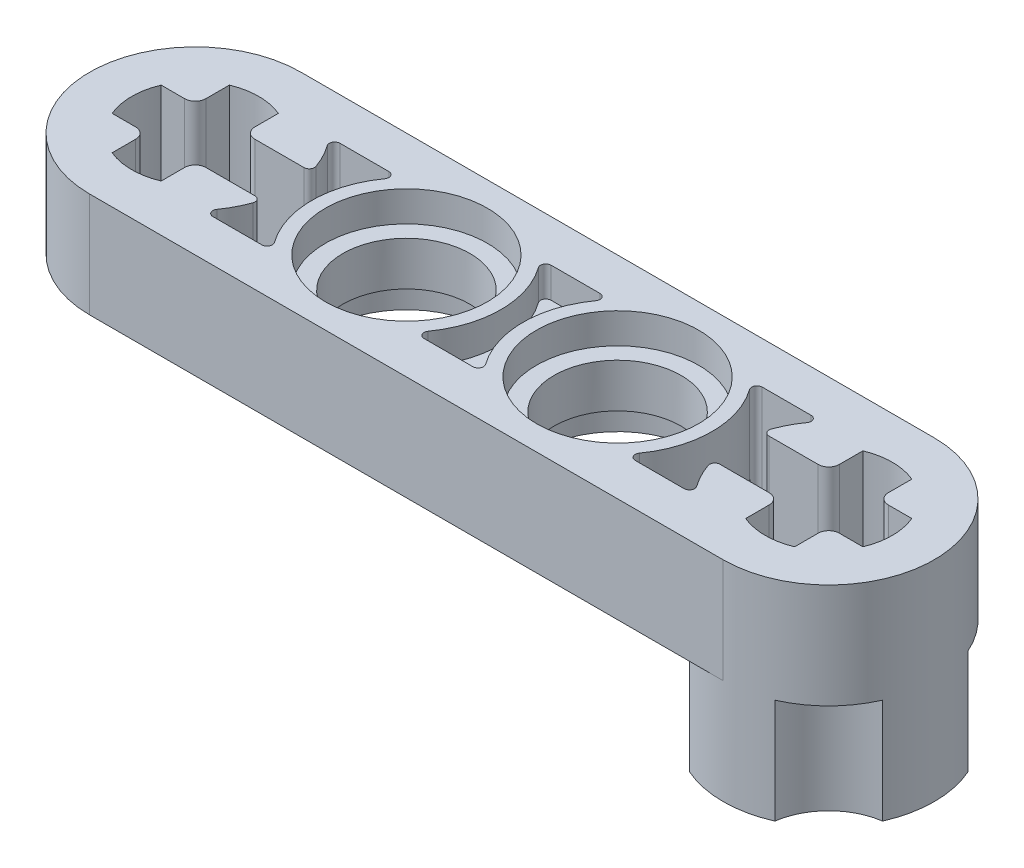
SolidWorks part; units mm, degrees
ref_plane "Front" through (0, 0, 0) normal (0, 0, 1) x (1, 0, 0)
ref_plane "Top" through (0, 0, 0) normal (0, 1, 0) x (1, 0, 0)
ref_plane "Right" through (0, 0, 0) normal (1, 0, 0) x (0, 0, -1)
sketch "Sketch1" plane through (0, 0, 0) normal (0, 1, 0) x (1, 0, 0)
  line L0 (0, 0) -> (0, 8.6394) construction
  line L1 (-11.9063, 3.9687) -> (11.9063, 3.9687)
  line L2 (11.9063, -3.9687) -> (-11.9063, -3.9687)
  line L3 (0, 0) -> (18.7139, 0) construction
  arc A0 (11.9063, 3.9687) -> (11.9063, -3.9687) centre (11.9063, 0) cw
  arc A1 (-11.9063, 3.9687) -> (-11.9063, -3.9687) centre (-11.9063, 0) ccw
  point P6 (0, 3.9687)
  point P11 (0, -3.9688)
  dimension "D1" = 7.9375
  dimension "D2" = 31.75
extrude "Base-Extrude" add sketch "Sketch1" along normal mid plane 3.937
sketch "Sketch2" plane through (0, 1.9685, 0) normal (0, 1, 0) x (-1, 0, 0)
  circle A0 centre (3.9688, 0) radius 2.3876
  dimension "D1" = 4.7752
  dimension "D2" = 3.9688
extrude "Cut-Extrude1" cut sketch "Sketch2" against normal through all
sketch "Sketch3" plane through (0, 1.9685, 0) normal (0, 1, 0) x (-1, 0, 0)
  circle A0 centre (3.9688, 0) radius 3.048
  dimension "D1" = 6.096
extrude "Cut-Extrude2" cut sketch "Sketch3" against normal blind 1.143
sketch "Sketch4" plane through (0, -1.9685, 0) normal (0, -1, 0) x (1, 0, 0)
  circle A0 centre (-3.9688, 0) radius 3.048
  dimension "D1" = 6.096
extrude "Cut-Extrude3" cut sketch "Sketch4" against normal blind 1.143
pattern_linear "LPattern1" count 2 spacing 7.9375 along (1, 0, 0) of "Cut-Extrude3", "Cut-Extrude2", "Cut-Extrude1"
sketch "Sketch5" plane through (0, 1.9685, 0) normal (0, 1, 0) x (-1, 0, 0)
  line L0 (11.9063, 0) -> (11.9063, -5.3472) construction
  line L1 (11.9063, 0) -> (8.2567, 0) construction
  line L2 (10.9855, -2.2029) -> (10.9855, -0.9207)
  line L3 (10.9855, -0.9207) -> (9.7033, -0.9207)
  line L4 (10.9855, 0.9208) -> (9.7033, 0.9208)
  line L5 (10.9855, 2.2029) -> (10.9855, 0.9208)
  line L6 (12.827, 2.2029) -> (12.827, 0.9208)
  line L7 (12.827, 0.9208) -> (14.1092, 0.9208)
  line L8 (12.827, -0.9207) -> (14.1092, -0.9207)
  line L9 (12.827, -2.2029) -> (12.827, -0.9207)
  arc A0 (10.9855, -2.2029) -> (12.827, -2.2029) centre (11.9063, 0) ccw
  arc A1 (9.7033, 0.9208) -> (9.7033, -0.9207) centre (11.9063, 0) ccw
  arc A2 (12.827, 2.2029) -> (10.9855, 2.2029) centre (11.9063, 0) ccw
  arc A3 (14.1092, -0.9207) -> (14.1092, 0.9208) centre (11.9063, 0) ccw
  dimension "D1" = 4.7752
  dimension "D2" = 0.9207
extrude "Cut-Extrude4" cut sketch "Sketch5" against normal through all
fillet "Fillet1" radius 0.3969 4 edges at (-10.9855, 0, 0.9208) (-12.827, 0, 0.9208) (-12.827, 0, -0.9207) (-10.9855, 0, -0.9207)
sketch "Sketch6" plane through (0, 1.9685, 0) normal (0, 1, 0) x (-1, 0, 0)
  line L0 (9.271, -2.3876) -> (6.604, -2.3876)
  line L1 (11.9063, 0) -> (3.9688, 0) construction
  line L2 (9.271, 2.3876) -> (6.604, 2.3876)
  line L3 (9.7033, -0.9207) -> (8.4715, -0.9207)
  line L4 (9.7033, 0.9208) -> (8.4715, 0.9208)
  circle A0 centre (3.9688, 0) radius 2.3876 construction
  arc A2 (6.604, -2.3876) -> (6.604, 2.3876) centre (3.9688, 0) ccw
  arc A3 (9.271, 2.3876) -> (8.4715, 0.9208) centre (11.9063, 0) ccw
  arc A4 (9.7033, 0.9208) -> (9.7033, -0.9207) centre (11.9063, 0) ccw construction
  arc A5 (9.7033, 0.9208) -> (9.7033, -0.9207) centre (11.9063, 0) ccw
  arc A6 (8.4715, -0.9207) -> (9.271, -2.3876) centre (11.9063, 0) ccw
  dimension "D2" = 7.112
extrude "Cut-Extrude5" cut sketch "Sketch6" against normal through all
fillet "Fillet2" radius 0.1984 6 edges at (-8.4715, 0, -0.9207) (-9.271, 0, -2.3876) (-6.604, 0, -2.3876) (-6.604, 0, 2.3876) (-9.271, 0, 2.3876) (-8.4715, 0, 0.9208)
mirror "Mirror1" about plane through (0, 0, 0) normal (1, 0, 0) of "Fillet2", "Cut-Extrude5", "Fillet1", "Cut-Extrude4"
sketch "Sketch7" plane through (7.6266, 1.9685, -1.7506) normal (0, 1, 0) x (-1, 0, 0)
  line L0 (8.9601, -0.637) -> (6.2931, -0.637)
  line L1 (11.5954, 1.7506) -> (3.6579, 1.7506) construction
  line L2 (8.9601, 4.1382) -> (6.2931, 4.1382)
  circle A0 centre (11.5954, 1.7506) radius 2.3876 construction
  circle A1 centre (3.6579, 1.7506) radius 2.3876 construction
  arc A2 (6.2931, -0.637) -> (6.2931, 4.1382) centre (3.6579, 1.7506) ccw
  arc A3 (8.9601, 4.1382) -> (8.0394, 1.7506) centre (11.5954, 1.7506) ccw
  arc A6 (8.0394, 1.7506) -> (8.9601, -0.637) centre (11.5954, 1.7506) ccw
  dimension "D2" = 7.112
extrude "Cut-Extrude6" cut sketch "Sketch7" against normal blind 1.143
fillet "Fillet3" radius 0.1984 4 edges at (-1.3335, 1.397, -2.3876) (1.3335, 1.397, -2.3876) (1.3335, 1.397, 2.3876) (-1.3335, 1.397, 2.3876)
mirror "Mirror2" about plane through (0, 0, 0) normal (0, 1, 0) of "Fillet3", "Cut-Extrude6"
sketch "Sketch8" plane through (0, -1.9685, 0) normal (0, -1, 0) x (1, 0, 0)
  circle A0 centre (11.9063, 0) radius 3.9687
  circle A1 centre (11.9063, 0) radius 2.3876
extrude "Boss-Extrude1" add sketch "Sketch8" along normal blind 3.937
sketch "Sketch9" plane through (0, -5.9055, 0) normal (0, -1, 0) x (1, 0, 0)
  line L0 (11.9063, 0) -> (11.9063, -4.7829) construction
  line L1 (11.9063, 0) -> (15.8424, -3.9361) construction
  circle A0 centre (15.875, -3.9687) radius 2.3876
  dimension "D2" = 4.7752
  dimension "D1" = 45
  dimension "D3" = 3.9688
extrude "Cut-Extrude7" cut sketch "Sketch9" against normal up to surface (3.937 mm away)
pattern_circular "CirPattern1" count 4 every 90 about axis through (11.9063, 0, 0) along (0, 1, 0) of "Cut-Extrude7"
